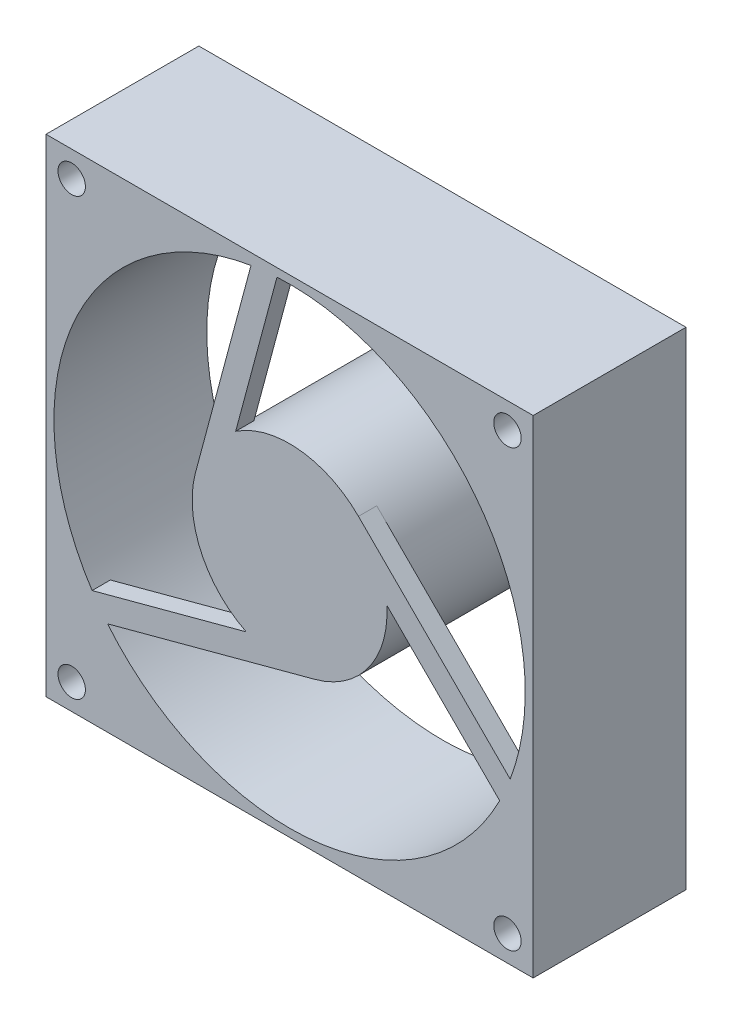
SolidWorks part; units mm, degrees
ref_plane "Front Plane" through (0, 0, 0) normal (0, 0, 1) x (1, 0, 0)
ref_plane "Top Plane" through (0, 0, 0) normal (0, 1, 0) x (1, 0, 0)
ref_plane "Right Plane" through (0, 0, 0) normal (1, 0, 0) x (0, 0, -1)
sketch "Sketch1" plane through (0, 0, 0) normal (0, 0, 1) x (1, 0, 0)
  line L1 (-40, -40) -> (40, -40)
  line L2 (-40, -40) -> (-40, 40)
  line L3 (-40, 40) -> (40, 40)
  line L4 (40, -40) -> (40, 40)
  line L5 (-40, -40) -> (40, 40) construction
  line L6 (-40, 40) -> (40, -40) construction
  line L7 (-35.7796, -35.7796) -> (35.7796, -35.7796) construction
  line L8 (-35.7796, -35.7796) -> (-35.7796, 35.7796) construction
  line L9 (-35.7796, 35.7796) -> (35.7796, 35.7796) construction
  line L10 (35.7796, -35.7796) -> (35.7796, 35.7796) construction
  line L11 (-35.7796, -35.7796) -> (35.7796, 35.7796) construction
  line L12 (-35.7796, 35.7796) -> (35.7796, -35.7796) construction
  circle A0 centre (-35.7796, 35.7796) radius 2.25
  circle A1 centre (35.7796, 35.7796) radius 2.25
  circle A2 centre (35.7796, -35.7796) radius 2.25
  circle A3 centre (-35.7796, -35.7796) radius 2.25
  circle A4 centre (0, 0) radius 38.7
  circle A5 centre (0, 0) radius 16
  point P0 (0, 0)
  point P6 (0, 0)
  point P15 (-34.1886, 34.1886)
  point P16 (34.1886, -34.1886)
  point P19 (0, 38.7)
  dimension "D2" = 4.5
  dimension "D5" = 32
  dimension "D1" = 80
  dimension "D3" = 96.7
  dimension "D4" = 1.3
extrude "Boss-Extrude1" add sketch "Sketch1" along normal mid plane 25.1 contours L1 L4 L3 L2 A4 A3 A2 A1 A0 | A5
sketch "Sketch2" plane through (0, 0, 12.55) normal (0, 0, 1) x (1, 0, 0)
  line L0 (-15.4548, 4.1411) -> (-6.3346, 38.178)
  line L1 (-8.852, 13.3282) -> (-2.0685, 38.6447)
  line L2 (0, -24.5293) -> (0, 31.2045) construction
  circle A0 centre (0, 0) radius 16 construction
  circle A1 centre (0, 0) radius 38.7 construction
  arc A3 (-6.3346, 38.178) -> (-2.0685, 38.6447) centre (0, 0) cw
  arc A4 (-15.4548, 4.1411) -> (-8.852, 13.3282) centre (0, 0) cw
  point P12 (4.0046, 15.4907)
  point P13 (-6.0241, 14.8226)
  dimension "D1" = 4
  dimension "D2" = 15
extrude "Boss-Extrude2" add sketch "Sketch2" against normal blind 3
pattern_circular "CirPattern1" count 3 over 360 about axis through (0, 0, 0) along (0, 0, 1) of "Boss-Extrude2"
